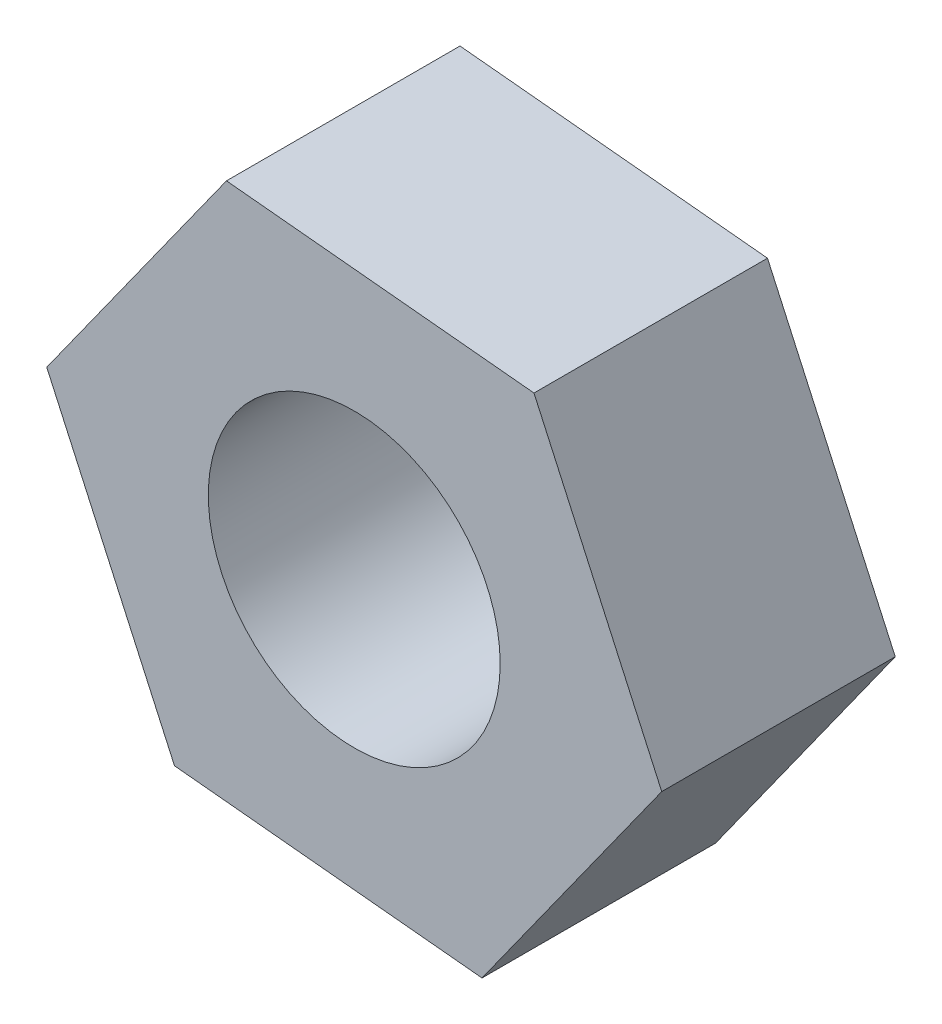
SolidWorks part; units mm, degrees
material "Acier non allié"
ref_plane "Plan de face" through (0, 0, 0) normal (0, 0, 1) x (1, 0, 0)
ref_plane "Plan de dessus" through (0, 0, 0) normal (0, 1, 0) x (1, 0, 0)
ref_plane "Plan de droite" through (0, 0, 0) normal (1, 0, 0) x (0, 0, -1)
sketch "Esquisse1" plane through (0, 0, 0) normal (0, 0, 1) x (1, 0, 0)
  line L1 (1.0076, 1.4088) -> (-0.7162, 1.577) construction
  line L2 (-0.7162, 1.577) -> (-1.7239, 0.1682) construction
  line L3 (-1.7239, 0.1682) -> (-1.0076, -1.4088) construction
  line L4 (-1.0076, -1.4088) -> (0.7162, -1.577) construction
  line L5 (0.7162, -1.577) -> (1.7239, -0.1682) construction
  line L6 (1.7239, -0.1682) -> (1.0076, 1.4088) construction
  line L7 (1.8473, 2.5828) -> (-1.3131, 2.8912)
  line L8 (-1.3131, 2.8912) -> (-3.1604, 0.3084)
  line L9 (-3.1604, 0.3084) -> (-1.8473, -2.5828)
  line L10 (-1.8473, -2.5828) -> (1.3131, -2.8912)
  line L11 (1.3131, -2.8912) -> (3.1604, -0.3084)
  line L12 (3.1604, -0.3084) -> (1.8473, 2.5828)
  circle A0 centre (0, 0) radius 1.5
  circle A1 centre (0, 0) radius 2.75 construction
  dimension "D2" = 3
  dimension "D1" = 5.5
extrude "Boss.-Extru.1" add sketch "Esquisse1" along normal blind 2.4
